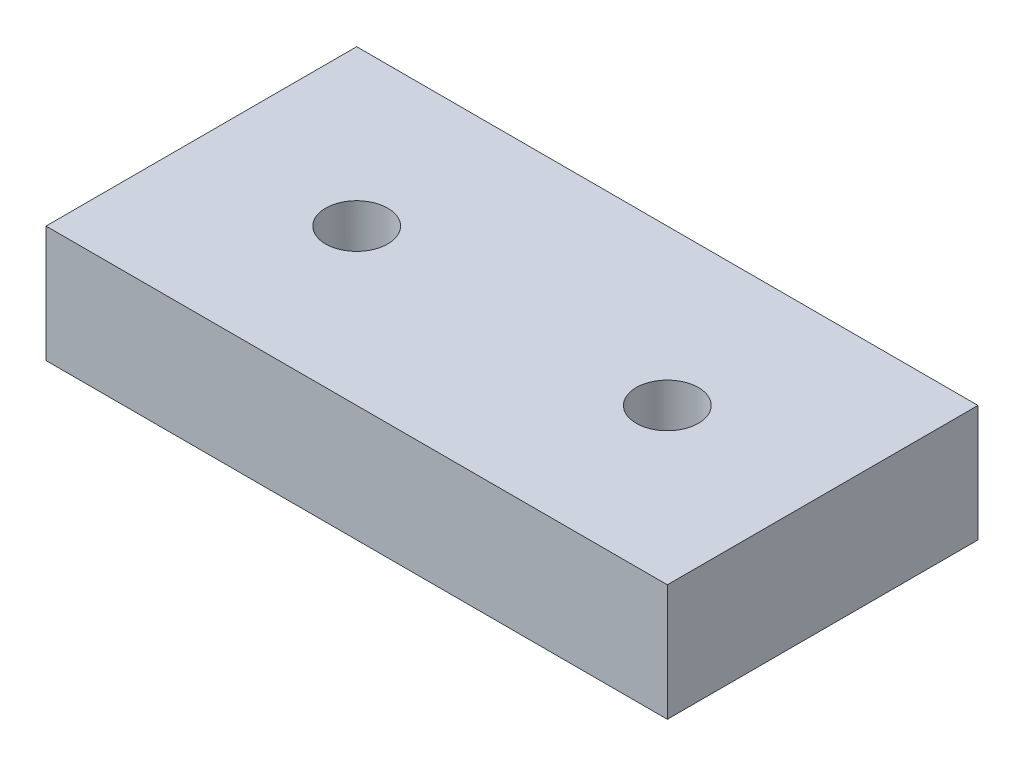
SolidWorks part; units mm, degrees
ref_plane "Alzado" through (0, 0, 0) normal (0, 0, 1) x (1, 0, 0)
ref_plane "Planta" through (0, 0, 0) normal (0, 1, 0) x (1, 0, 0)
ref_plane "Vista lateral" through (0, 0, 0) normal (1, 0, 0) x (0, 0, -1)
sketch "Croquis1" plane through (0, 0, 0) normal (0, 1, 0) x (1, 0, 0)
  line L1 (20, 10) -> (-20, 10)
  line L2 (20, 10) -> (20, -10)
  line L3 (20, -10) -> (-20, -10)
  line L4 (-20, 10) -> (-20, -10)
  line L5 (20, 10) -> (-20, -10) construction
  line L6 (20, -10) -> (-20, 10) construction
  circle A0 centre (-10, 0) radius 2
  circle A1 centre (10, 0) radius 2
  point P0 (0, 0)
  dimension "D1" = 4
  dimension "D2" = 4
  dimension "D3" = 40
  dimension "D4" = 20
  dimension "D5" = 10
  dimension "D6" = 10
extrude "Saliente-Extruir1" add sketch "Croquis1" along normal blind 7.5
sketch "Croquis2" plane through (0, 0, 0) normal (0, -1, 0) x (1, 0, 0)
  circle A0 centre (-10, 0) radius 6
  circle A3 centre (10, 0) radius 6
  dimension "D1" = 12
  dimension "D2" = 12
extrude "Cortar-Extruir1" cut sketch "Croquis2" against normal blind 4
shell "Vaciado3" thickness 1
fillet "Redondeo1" radius 4 4 edges at (-19, 3.25, -9) (19, 3.25, -9) (19, 3.25, 9) (-19, 3.25, 9)
